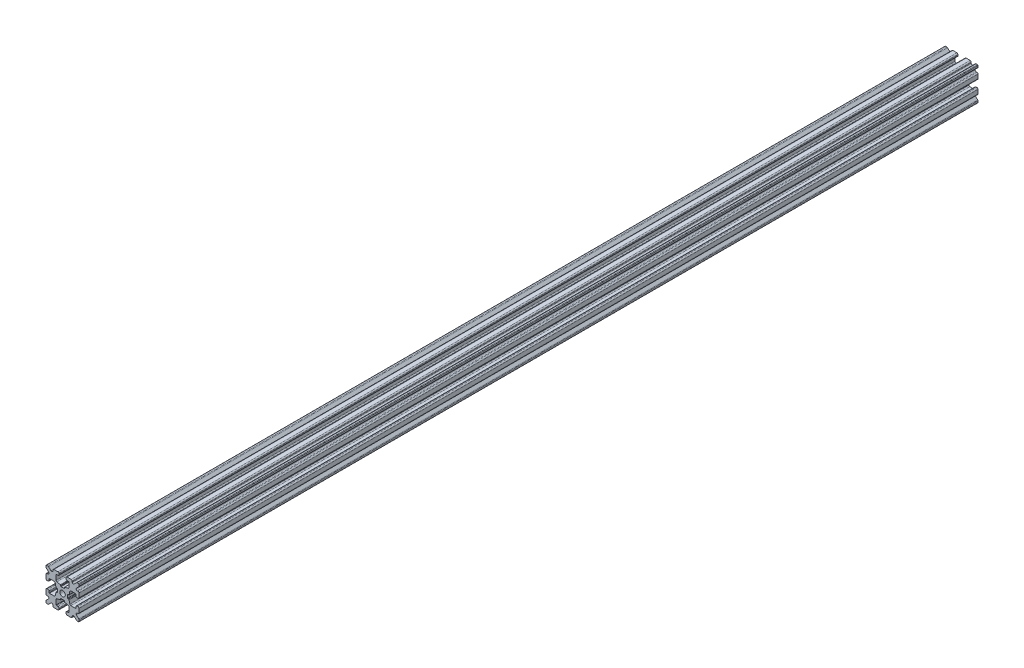
SolidWorks part; units mm, degrees
material "1060 Alloy"
ref_plane "Front Plane" through (0, 0, 0) normal (0, 0, 1) x (1, 0, 0)
ref_plane "Top Plane" through (0, 0, 0) normal (0, 1, 0) x (1, 0, 0)
ref_plane "Right Plane" through (0, 0, 0) normal (1, 0, 0) x (0, 0, -1)
sketch "Sketch1" plane through (0, 0, 0) normal (0, 0, 1) x (1, 0, 0)
  line L1 (-7.5, -7.5) -> (7.5, -7.5)
  line L2 (-7.5, -7.5) -> (-7.5, 7.5)
  line L3 (-7.5, 7.5) -> (7.5, 7.5)
  line L4 (7.5, -7.5) -> (7.5, 7.5)
  line L5 (-7.5, -7.5) -> (7.5, 7.5) construction
  line L6 (-7.5, 7.5) -> (7.5, -7.5) construction
  circle A0 centre (0, 0) radius 1.25
  point P0 (0, 0)
  dimension "D2" = 2.5
  dimension "D1" = 15
extrude "Boss-Extrude1" add sketch "Sketch1" along normal mid plane 408
fillet "Fillet1" radius 0.25 4 edges at (7.5, -7.5, 0) (-7.5, -7.5, 0) (7.5, 7.5, 0) (-7.5, 7.5, 0)
sketch "Sketch2" plane through (0, 0, 204) normal (0, 0, 1) x (1, 0, 0)
  line L0 (-7.5, 7.25) -> (-7.5, -7.25) construction
  line L1 (-7.5, 1.6) -> (-6.1, 1.6)
  line L2 (-7.5, 1.6) -> (-7.5, -1.6)
  line L3 (-7.5, -1.6) -> (-6.1, -1.6)
  line L4 (-6.1, 1.6) -> (-6.1, 2.9)
  line L5 (0, 0) -> (-12.1036, 0) construction
  line L6 (-6.1, -2.9) -> (-3.4, -2.9)
  line L7 (0, 0) -> (-7.25, 7.25) construction
  line L8 (-6.1, 2.9) -> (-3.4, 2.9)
  line L9 (-3.4, -2.9) -> (-3.4, 2.9)
  line L10 (55, 0) -> (-55, 0) construction
  line L11 (-6.1, -2.9) -> (-6.1, -1.6)
  line L12 (2.9, 6.1) -> (1.6, 6.1)
  line L13 (2.9, 3.4) -> (-2.9, 3.4)
  line L14 (-2.9, 6.1) -> (-2.9, 3.4)
  line L15 (2.9, 6.1) -> (2.9, 3.4)
  line L16 (-1.6, 6.1) -> (-2.9, 6.1)
  line L17 (1.6, 7.5) -> (1.6, 6.1)
  line L18 (-1.6, 7.5) -> (1.6, 7.5)
  line L19 (-1.6, 7.5) -> (-1.6, 6.1)
  line L20 (-1.6, -7.5) -> (-1.6, -6.1)
  line L21 (-1.6, -7.5) -> (1.6, -7.5)
  line L22 (1.6, -7.5) -> (1.6, -6.1)
  line L23 (-1.6, -6.1) -> (-2.9, -6.1)
  line L24 (2.9, -6.1) -> (2.9, -3.4)
  line L25 (-2.9, -6.1) -> (-2.9, -3.4)
  line L26 (2.9, -3.4) -> (-2.9, -3.4)
  line L27 (2.9, -6.1) -> (1.6, -6.1)
  line L28 (6.1, -2.9) -> (6.1, -1.6)
  line L29 (3.4, -2.9) -> (3.4, 2.9)
  line L30 (6.1, 2.9) -> (3.4, 2.9)
  line L31 (6.1, -2.9) -> (3.4, -2.9)
  line L32 (6.1, 1.6) -> (6.1, 2.9)
  line L33 (7.5, -1.6) -> (6.1, -1.6)
  line L34 (7.5, 1.6) -> (7.5, -1.6)
  line L35 (7.5, 1.6) -> (6.1, 1.6)
  dimension "D1" = 3.2
  dimension "D2" = 5.8
  dimension "D3" = 1.4
  dimension "D4" = 2.7
extrude "Cut-Extrude1" cut sketch "Sketch2" against normal through all
sketch "Sketch4" plane through (0, 0, 204) normal (0, 0, 1) x (1, 0, 0)
  line L0 (-3.4, 2.9) -> (-2.75, 0)
  line L1 (55, 0) -> (-55, 0) construction
  line L2 (-2.75, 0) -> (-3.4, -2.9)
  line L3 (-3.4, -2.9) -> (-3.4, 2.9) construction
  line L4 (-3.4, 2.9) -> (-3.4, -2.9)
  line L5 (-2.9, 3.4) -> (0, 2.75)
  line L6 (0, 2.75) -> (2.9, 3.4)
  line L7 (2.9, 3.4) -> (-2.9, 3.4)
  line L8 (3.4, 2.9) -> (2.75, 0)
  line L9 (2.75, 0) -> (3.4, -2.9)
  line L10 (3.4, -2.9) -> (3.4, 2.9)
  line L11 (-2.9, -3.4) -> (0, -2.75)
  line L12 (0, -2.75) -> (2.9, -3.4)
  line L13 (2.9, -3.4) -> (-2.9, -3.4)
  circle A2 centre (0, 0) radius 2.75
  circle A3 centre (0, 0) radius 2.75 construction
  dimension "D1" = 1.5
extrude "Cut-Extrude3" cut sketch "Sketch4" against normal through all
fillet "Fillet3" radius 0.5 16 edges at (-6.1, -1.6, 0) (-7.5, -1.6, 0) (-6.1, 1.6, 0) (-7.5, 1.6, 0) (-1.6, -7.5, 0) (-1.6, -6.1, 0) (1.6, -7.5, 0) (1.6, -6.1, 0) (6.1, -1.6, 0) (7.5, -1.6, 0) (7.5, 1.6, 0) (6.1, 1.6, 0) (1.6, 7.5, 0) (1.6, 6.1, 0) (-1.6, 7.5, 0) (-1.6, 6.1, 0)
fillet "Fillet4" radius 0.5 8 edges at (-3.4, 2.9, 0) (-3.4, -2.9, 0) (2.9, -3.4, 0) (-2.9, -3.4, 0) (3.4, -2.9, 0) (3.4, 2.9, 0) (-2.9, 3.4, 0) (2.9, 3.4, 0)
fillet "Fillet5" radius 3 4 edges at (0, -2.75, 0) (2.75, 0, 0) (-2.75, 0, 0) (0, 2.75, 0)
fillet "Fillet6" radius 0.2 8 edges at (-2.9, -6.1, 0) (2.9, -6.1, 0) (6.1, -2.9, 0) (6.1, 2.9, 0) (2.9, 6.1, 0) (-2.9, 6.1, 0) (-6.1, -2.9, 0) (-6.1, 2.9, 0)
sketch "Sketch5" plane through (0, 0, 204) normal (0, 0, 1) x (1, 0, 0)
  line L0 (0, 0) -> (-7.25, 7.25) construction
  line L1 (-7.5, 6.4393) -> (-5.4607, 4.4)
  line L2 (-6.4393, 7.5) -> (-4.4, 5.4607)
  line L3 (-7.5, 4.4) -> (-5.4607, 4.4)
  line L4 (-3.8003, 2.9) -> (-5.9, 2.9) construction
  line L5 (0, 0) -> (-12.1819, 0) construction
  line L6 (-4.4, 7.5) -> (-4.4, 5.4607)
  line L7 (-2.9, 5.9) -> (-2.9, 3.8003) construction
  line L8 (-7.5, 6.4393) -> (-7.5, 4.4)
  line L9 (-7.5, 7.25) -> (-7.5, 2.1) construction
  line L10 (2.1, -7.5) -> (7.25, -7.5) construction
  line L11 (7.5, -7.25) -> (7.5, -2.1) construction
  line L12 (7.25, 7.5) -> (2.1, 7.5) construction
  line L13 (-2.1, 7.5) -> (-7.25, 7.5) construction
  line L14 (-4.4, 7.5) -> (-6.4393, 7.5)
  line L16 (55, 0) -> (-55, 0) construction
  line L17 (0, 0) -> (0, 10.993) construction
  line L18 (0, -54.6431) -> (0, 54.6431) construction
  line L20 (4.4, 7.5) -> (6.4393, 7.5)
  line L22 (7.5, 6.4393) -> (7.5, 4.4)
  line L23 (4.4, 7.5) -> (4.4, 5.4607)
  line L24 (7.5, 4.4) -> (5.4607, 4.4)
  line L25 (6.4393, 7.5) -> (4.4, 5.4607)
  line L26 (7.5, 6.4393) -> (5.4607, 4.4)
  line L27 (7.5, -6.4393) -> (5.4607, -4.4)
  line L28 (6.4393, -7.5) -> (4.4, -5.4607)
  line L29 (7.5, -4.4) -> (5.4607, -4.4)
  line L30 (4.4, -7.5) -> (4.4, -5.4607)
  line L31 (7.5, -6.4393) -> (7.5, -4.4)
  line L33 (4.4, -7.5) -> (6.4393, -7.5)
  line L36 (-4.4, -7.5) -> (-6.4393, -7.5)
  line L38 (-7.5, -6.4393) -> (-7.5, -4.4)
  line L39 (-4.4, -7.5) -> (-4.4, -5.4607)
  line L40 (-7.5, -4.4) -> (-5.4607, -4.4)
  line L41 (-6.4393, -7.5) -> (-4.4, -5.4607)
  line L42 (-7.5, -6.4393) -> (-5.4607, -4.4)
  dimension "D1" = 1.5
  dimension "D2" = 1.5
  dimension "D3" = 1.5
extrude "Cut-Extrude4" cut sketch "Sketch5" against normal through all
fillet "Fillet8" radius 0.5 24 edges at (-5.4607, 4.4, 0) (-7.5, 4.4, 0) (-5.4607, -4.4, 0) (-7.5, -4.4, 0) (-4.4, -7.5, 0) (-4.4, -5.4607, 0) (4.4, -7.5, 0) (4.4, -5.4607, 0) (5.4607, -4.4, 0) (7.5, -4.4, 0) (7.5, 4.4, 0) (5.4607, 4.4, 0) (4.4, 5.4607, 0) (4.4, 7.5, 0) (-4.4, 5.4607, 0) (-4.4, 7.5, 0) (-6.4393, 7.5, 0) (-7.5, 6.4393, 0) (6.4393, 7.5, 0) (7.5, 6.4393, 0) (6.4393, -7.5, 0) (7.5, -6.4393, 0) (-6.4393, -7.5, 0) (-7.5, -6.4393, 0)
sketch "Sketch6" plane through (0, 0, 204) normal (0, 0, 1) x (1, 0, 0)
  line L0 (0, 0) -> (0, 11.013) construction
  line L1 (0.6561, 2.8971) -> (2.1235, 2.8971) construction
  line L2 (0, -54.6431) -> (0, 54.6431) construction
  line L3 (0, 0) -> (7.25, 7.25) construction
  line L4 (7.5, 0.8255) -> (7.5, -0.8255)
  line L5 (2.3471, 0.8255) -> (7.5, 0.8255)
  line L6 (0, 0) -> (12.4016, 0) construction
  line L7 (0.8255, -7.5) -> (-0.8255, -7.5)
  line L8 (2.3471, -0.8255) -> (2.3471, 0.8255)
  line L9 (0.8255, -2.3471) -> (0.8255, -7.5)
  line L10 (7.5, -0.8255) -> (2.3471, -0.8255)
  line L11 (-7.5, -0.8255) -> (-2.3471, -0.8255)
  line L12 (-2.3471, -0.8255) -> (-2.3471, 0.8255)
  line L13 (-0.8255, -2.3471) -> (0.8255, -2.3471)
  line L14 (-0.8255, 7.5) -> (-0.8255, 2.3471)
  line L15 (-0.8255, 2.3471) -> (0.8255, 2.3471)
  line L16 (-0.8255, -7.5) -> (-0.8255, -2.3471)
  line L17 (0.8255, 2.3471) -> (0.8255, 7.5)
  line L18 (0.8255, 7.5) -> (-0.8255, 7.5)
  line L19 (3.9, 7.5) -> (2.1, 7.5) construction
  line L20 (-2.3471, 0.8255) -> (-7.5, 0.8255)
  line L21 (-7.5, 0.8255) -> (-7.5, -0.8255)
  point P5 (0, -2.5973)
  point P7 (0, 2.5973)
  dimension "D3" = 0.55
  dimension "D1" = 1.651
extrude "Cut-Extrude5" cut sketch "Sketch6" against normal through all
fillet "Fillet10" radius 0.2 16 edges at (-2.935, 0.8255, 0) (-2.935, -0.8255, 0) (2.935, -0.8255, 0) (2.935, 0.8255, 0) (0.8255, 2.935, 0) (-0.8255, 2.935, 0) (-2.3471, 0.8255, 0) (-2.3471, -0.8255, 0) (0.8255, 2.3471, 0) (-0.8255, 2.3471, 0) (2.3471, 0.8255, 0) (2.3471, -0.8255, 0) (0.8255, -2.935, 0) (0.8255, -2.3471, 0) (-0.8255, -2.3471, 0) (-0.8255, -2.935, 0)
